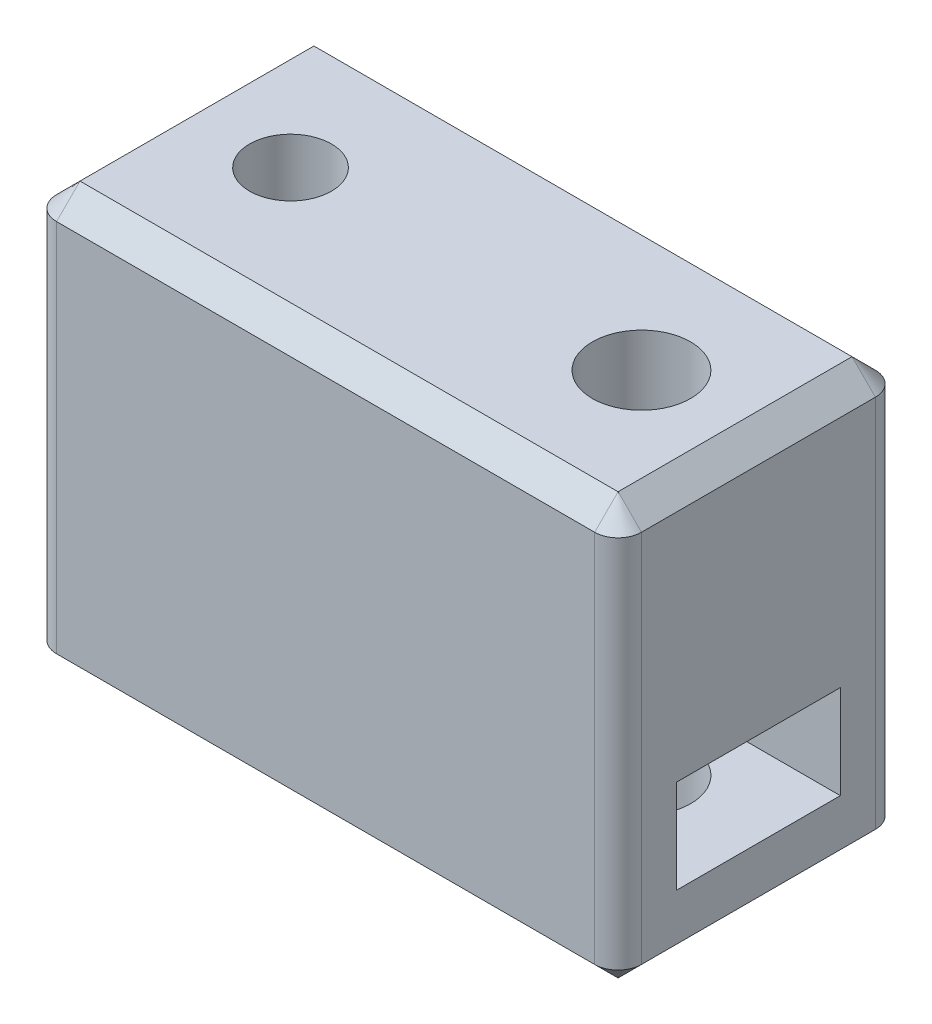
SolidWorks part; units mm, degrees
ref_plane "Front Plane" through (0, 0, 0) normal (0, 0, 1) x (1, 0, 0)
ref_plane "Top Plane" through (0, 0, 0) normal (0, 1, 0) x (1, 0, 0)
ref_plane "Right Plane" through (0, 0, 0) normal (1, 0, 0) x (0, 0, -1)
sketch "Sketch2" plane through (0, 0, 0) normal (0, 1, 0) x (1, 0, 0)
  line L0 (-7.5, 0) -> (7.5, 0) construction
  line L1 (-12.5, 6) -> (12.5, 6)
  line L2 (-12.5, 6) -> (-12.5, -6)
  line L3 (-12.5, -6) -> (12.5, -6)
  line L4 (12.5, 6) -> (12.5, -6)
  line L5 (-12.5, 6) -> (12.5, -6) construction
  line L6 (-12.5, -6) -> (12.5, 6) construction
  circle A0 centre (-7.5, 0) radius 1.75
  circle A1 centre (7.5, 0) radius 2.1
  point P0 (0, 0)
  dimension "D2" = 3.5
  dimension "D3" = 4.2
  dimension "D1" = 12
  dimension "D4" = 5
  dimension "D5" = 15
extrude "Boss-Extrude1" add sketch "Sketch2" along normal blind 18
sketch "Sketch7" plane through (12.5, 0, 0) normal (1, 0, 0) x (0, 0, -1)
  line L0 (0, 0) -> (0, 18) construction
  line L1 (-6, 18) -> (6, 18) construction
  line L2 (-6, 0) -> (6, 0) construction
  line L3 (-3.5, 7) -> (3.5, 7)
  line L4 (-3.5, 7) -> (-3.5, 3)
  line L5 (-3.5, 3) -> (3.5, 3)
  line L6 (3.5, 7) -> (3.5, 3)
  line L7 (-3.5, 7) -> (3.5, 3) construction
  line L8 (-3.5, 3) -> (3.5, 7) construction
  point P5 (0, 5)
  dimension "D1" = 4
  dimension "D2" = 7
  dimension "D3" = 3
extrude "Cut-Extrude3" cut sketch "Sketch7" against normal blind 10
sketch "Sketch9" plane through (-12.5, 0, 0) normal (-1, 0, 0) x (0, 0, 1)
  line L0 (3.5, 3) -> (-3.5, 3) construction
  line L1 (-2.75, 3) -> (2.75, 3)
  line L2 (-2.75, 3) -> (-2.75, 6)
  line L3 (-2.75, 6) -> (2.75, 6)
  line L4 (2.75, 3) -> (2.75, 6)
  line L5 (-2.75, 3) -> (2.75, 6) construction
  line L6 (-2.75, 6) -> (2.75, 3) construction
  line L7 (0, 0) -> (0, 18) construction
  line L8 (-6, 18) -> (6, 18) construction
  point P0 (0, 4.5)
  dimension "D1" = 3
  dimension "D2" = 5.5
extrude "Cut-Extrude4" cut sketch "Sketch9" against normal blind 8
fillet "Fillet1" radius 1 4 edges at (-12.5, 9, 6) (-12.5, 9, -6) (12.5, 9, -6) (12.5, 9, 6)
chamfer "Chamfer1" distance 1 angle 45 16 edges at (0, 0, -6) (-12.2071, 0, -5.7071) (12.2071, 0, -5.7071) (-12.5, 0, 0) (12.5, 0, 0) (-12.2071, 0, 5.7071) (12.2071, 0, 5.7071) (0, 0, 6) (0, 18, -6) (-12.2071, 18, -5.7071) (12.2071, 18, -5.7071) (-12.5, 18, 0) (12.5, 18, 0) (-12.2071, 18, 5.7071) (12.2071, 18, 5.7071) (0, 18, 6)
